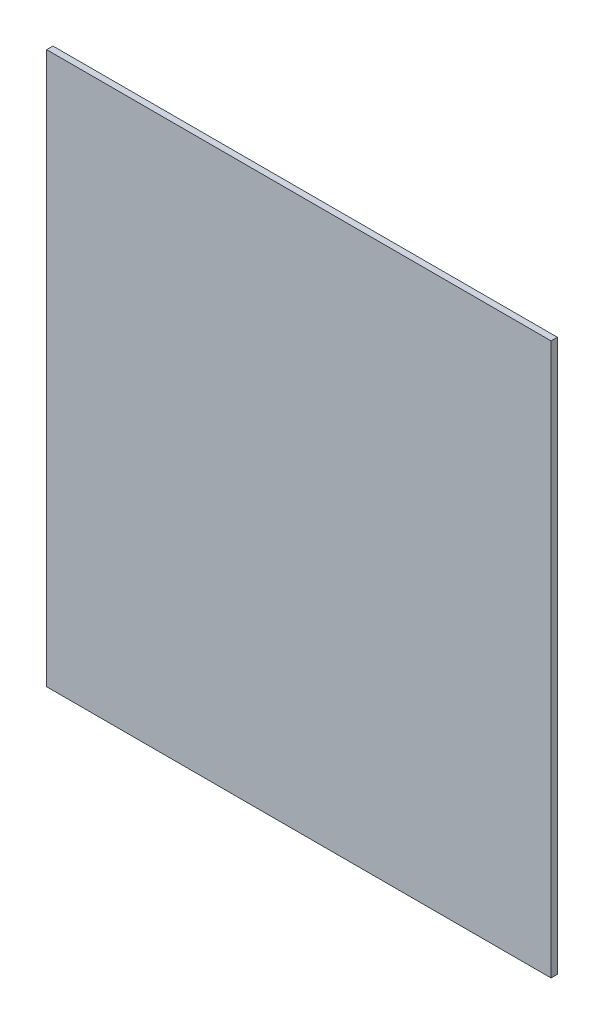
SolidWorks part; units mm, degrees
ref_plane "Front Plane" through (0, 0, 0) normal (0, 0, 1) x (1, 0, 0)
ref_plane "Top Plane" through (0, 0, 0) normal (0, 1, 0) x (1, 0, 0)
ref_plane "Right Plane" through (0, 0, 0) normal (1, 0, 0) x (0, 0, -1)
sketch "Sketch1" plane through (0, 0, 0) normal (0, 0, 1) x (1, 0, 0)
  line L1 (-52.2088, 16.5) -> (11.7912, 16.5)
  line L2 (-52.2088, 16.5) -> (-52.2088, -53.5)
  line L3 (-52.2088, -53.5) -> (11.7912, -53.5)
  line L4 (11.7912, 16.5) -> (11.7912, -53.5)
  dimension "D1" = 70
  dimension "D2" = 64
extrude "Boss-Extrude1" add sketch "Sketch1" along normal blind 0.8
